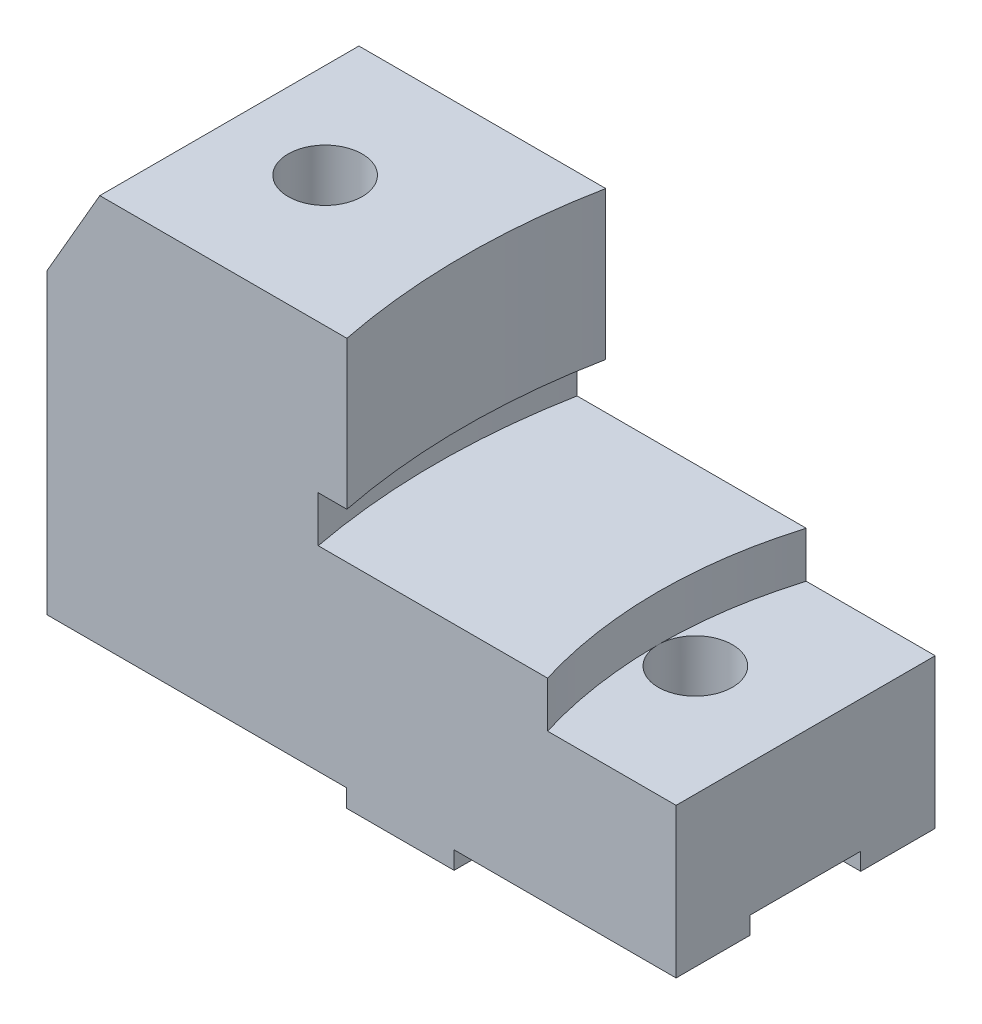
SolidWorks part; units mm, degrees
ref_plane "Front Plane" through (0, 0, 0) normal (0, 0, 1) x (1, 0, 0)
ref_plane "Top Plane" through (0, 0, 0) normal (0, 1, 0) x (1, 0, 0)
ref_plane "Right Plane" through (0, 0, 0) normal (1, 0, 0) x (0, 0, -1)
sketch "Sketch1" plane through (0, 0, 0) normal (0, 1, 0) x (1, 0, 0)
  line L0 (-51.43, 22.9236) -> (56.52, 22.9236)
  line L1 (56.52, 22.9236) -> (56.52, -21.5264)
  line L2 (56.52, -21.5264) -> (-51.43, -21.5264)
  line L3 (-51.43, 22.9236) -> (-51.43, -21.5264)
  dimension "D1" = 107.95
  dimension "D2" = 107.95
  dimension "D3" = 44.45
  dimension "D4" = 44.45
extrude "Boss-Extrude1" add sketch "Sketch1" along normal blind 69.85
sketch "Sketch2" plane through (56.52, 0, 0) normal (1, 0, 0) x (0, 0, -1)
  line L0 (-21.5264, 0) -> (-8.8264, 0)
  line L1 (-21.5264, 0) -> (22.9236, 0) construction
  line L2 (-8.8264, 0) -> (-8.8264, 6.0482)
  line L3 (-8.8264, 6.0482) -> (10.1476, 6.0482)
  line L4 (10.1476, 6.0482) -> (10.1476, 0)
  line L5 (-8.8264, 0) -> (10.1476, 0)
  dimension "D1" = 12.7
extrude "Cut-Extrude1" cut sketch "Sketch2" against normal blind 141.986 contours L5 L4 L3 L2
sketch "Sketch3" plane through (0, 0, 21.5264) normal (0, 0, 1) x (1, 0, 0)
  line L0 (56.52, 0) -> (18.4398, 0)
  line L1 (-51.43, 0) -> (56.52, 0) construction
  line L2 (18.4398, 0) -> (18.4398, 3.0508)
  line L3 (18.4398, 3.0508) -> (56.52, 3.0508)
  line L4 (56.52, 69.85) -> (56.52, 0) construction
  line L5 (56.52, 3.0508) -> (56.52, 0)
  line L6 (-51.43, 3.0508) -> (0, 3.0508)
  line L7 (-51.43, 69.85) -> (-51.43, 0) construction
  line L8 (0, 3.0508) -> (0, 0)
  line L9 (0, 0) -> (-51.43, 0)
  line L10 (-51.43, 0) -> (-51.43, 3.0508)
  dimension "D1" = 38.0802
extrude "Cut-Extrude3" cut sketch "Sketch3" against normal blind 141.986 contours L6 L8 L9 L10 | L0 L2 L3 L5
sketch "Sketch7" plane through (0, 0, 21.5264) normal (0, 0, 1) x (1, 0, 0)
  line L0 (-51.43, 54.102) -> (-42.3379, 69.85)
  line L1 (-51.43, 69.85) -> (-51.43, 3.0508) construction
  line L2 (-51.43, 69.85) -> (56.52, 69.85) construction
  line L3 (-51.43, 69.85) -> (-42.3379, 69.85)
  line L4 (-51.43, 69.85) -> (-51.43, 54.102)
  dimension "D1" = 15.748
  dimension "D2" = 30
extrude "Cut-Extrude4" cut sketch "Sketch7" against normal blind 141.986
sketch "Sketch8" plane through (0, 69.85, 0) normal (0, 1, 0) x (1, 0, 0)
  circle A0 centre (112.146, 0.8256) radius 114.3
  point P5 (106.8695, 26.4067)
  dimension "D1" = 228.6
  dimension "D2" = 163.576
  dimension "D3" = 22.352
extrude "Cut-Extrude6" cut sketch "Sketch8" against normal blind 33.274 contours A0
sketch "Sketch12" plane through (0, 36.576, 0) normal (0, 1, 0) x (1, 0, 0)
  circle A0 centre (112.146, 0.8256) radius 119.126
  dimension "D1" = 238.252
  dimension "D2" = 163.576
  dimension "D3" = 22.352
extrude "Cut-Extrude7" cut sketch "Sketch12" along normal blind 7.874 contours A0
sketch "Sketch13" plane through (0, 36.576, 0) normal (0, 1, 0) x (1, 0, 0)
  line L0 (56.52, -21.5264) -> (56.52, 22.9236) construction
  line L2 (-4.8642, -21.5264) -> (56.52, -21.5264) construction
  circle A0 centre (37.47, 0.8256) radius 6.35
  point P6 (36.9993, -21.5264)
  point P7 (34.7293, -18.839)
  dimension "D1" = 12.7
  dimension "D2" = 19.05
  dimension "D3" = 22.352
extrude "Cut-Extrude8" cut sketch "Sketch13" against normal blind 20.574 contours A0
sketch "Sketch14" plane through (0, 36.576, 0) normal (0, 1, 0) x (1, 0, 0)
  line L0 (-51.43, 22.9236) -> (-51.43, -21.5264) construction
  circle A0 centre (107.32, 0.8256) radius 76.2
  dimension "D1" = 152.4
  dimension "D2" = 22.352
  dimension "D3" = 158.75
extrude "Cut-Extrude9" cut sketch "Sketch14" against normal blind 7.874 contours A0
sketch "Sketch15" plane through (0, 69.85, 0) normal (0, 1, 0) x (1, 0, 0)
  line L0 (56.52, -21.5264) -> (56.52, 22.9236) construction
  line L1 (-42.3379, -21.5264) -> (0.0528, -21.5264) construction
  circle A0 centre (-26.03, 0.8256) radius 6.35
  point P6 (-79.4156, 44.3947)
  dimension "D1" = 12.7
  dimension "D2" = 82.55
  dimension "D3" = 22.352
extrude "Cut-Extrude10" cut sketch "Sketch15" against normal blind 20.574 contours A0
sketch "Sketch16" plane through (0, 69.85, 0) normal (0, 1, 0) x (1, 0, 0)
  line L0 (56.52, -21.5264) -> (56.52, 22.9236) construction
  line L1 (-51.43, -21.5264) -> (0, -21.5264) construction
  line L2 (34.472, -21.5264) -> (56.52, -21.5264) construction
  circle A0 centre (-26.03, 0.8256) radius 4.826
  circle A1 centre (37.47, 0.8256) radius 4.826
  point P4 (-25.715, -21.5264)
  dimension "D1" = 9.652
  dimension "D4" = 9.652
  dimension "D2" = 82.55
  dimension "D3" = 22.352
  dimension "D5" = 22.352
  dimension "D6" = 19.05
extrude "Cut-Extrude11" cut sketch "Sketch16" against normal blind 81.28 contours A1 | A0
